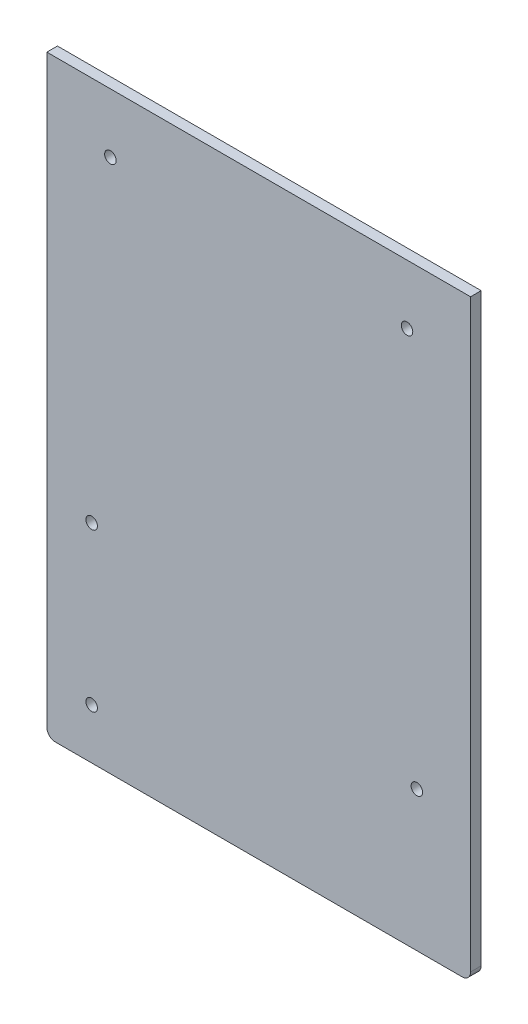
SolidWorks part; units mm, degrees
material "Acrylic (Medium-high impact)"
ref_plane "Front Plane" through (0, 0, 0) normal (0, 0, 1) x (1, 0, 0)
ref_plane "Top Plane" through (0, 0, 0) normal (0, 1, 0) x (1, 0, 0)
ref_plane "Right Plane" through (0, 0, 0) normal (1, 0, 0) x (0, 0, -1)
sketch "Sketch1" plane through (0, 0, 0) normal (0, 0, 1) x (1, 0, 0)
  line L1 (-134.9877, 109.7446) -> (-7.9877, 109.7446)
  line L2 (-134.9877, 109.7446) -> (-134.9877, -68.0554)
  line L3 (-134.9877, -68.0554) -> (-7.9877, -68.0554)
  line L4 (-7.9877, 109.7446) -> (-7.9877, -68.0554)
  dimension "D1" = 177.8
  dimension "D2" = 127
extrude "Boss-Extrude1" add sketch "Sketch1" along normal blind 3.175
sketch "Sketch8" plane through (0, 0, 3.175) normal (0, 0, 1) x (1, 0, 0)
  line L0 (-121.5503, -52.9588) -> (-121.5503, -5.7148) construction
  line L1 (-121.5503, -5.7148) -> (-24.0915, -26.1003) construction
  line L2 (-24.0915, -26.1003) -> (-121.5503, -52.9588) construction
  line L3 (-134.9877, 109.7446) -> (-134.9877, -68.0554) construction
  line L4 (-134.9877, -68.0554) -> (-7.9877, -68.0554) construction
  point P10 (-121.5503, -5.7148)
  point P11 (-121.5503, -52.9588)
  point P12 (-24.0915, -26.1003)
  dimension "D1" = 13.4374
  dimension "D2" = 97.4588
  dimension "D3" = 20.3855
  dimension "D4" = 15.0967
  dimension "D5" = 47.244
hole_wizard "#29 (0.136) Diameter Hole1" positions "Sketch9" profile "Sketch10" hole size "#29" standard "ANSI Inch" end condition through all
sketch "Sketch9" plane through (0, 0, 3.175) normal (0, 0, 1) x (1, 0, 0)
  line L0 (-115.9377, 91.9646) -> (-27.0377, 91.9646) construction
  line L2 (-71.4877, 91.9646) -> (-71.4877, 109.7446) construction
  line L3 (-7.9877, 109.7446) -> (-134.9877, 109.7446) construction
  point P69 (-27.0377, 91.9646)
  point P72 (-115.9377, 91.9646)
  dimension "D1" = 88.9
  dimension "D2" = 17.78
sketch "Sketch10" plane through (-27.0377, 91.9646, 3.175) normal (1, 0, 0) x (0, -1, 0)
  line L0 (0, 0) -> (0, 3.175)
  line L1 (0, 3.175) -> (1.7272, 3.175)
  line L2 (1.7272, 3.175) -> (1.7272, 0)
  line L5 (1.7272, 0) -> (0, 0)
  line L11 (0, -6.35) -> (0, 107.95) construction
  dimension "Thru Hole Dia." = 3.4544
  dimension "Thru Hole Depth" = 3.175
fillet "Fillet1" radius 2.54 2 edges at (-134.9877, -68.0554, 1.5875) (-7.9877, -68.0554, 1.5875)
hole_wizard "Tap Drill for #8-32 Tap1" positions "Sketch11" profile "Sketch12" hole size "#8-32" standard "ANSI Inch" end condition through all
sketch "Sketch11" plane through (0, 0, 3.175) normal (0, 0, 1) x (1, 0, 0)
  point P0 (-121.5503, -52.9588)
  point P3 (-121.5503, -5.7148)
  point P6 (-24.0915, -26.1003)
sketch "Sketch12" plane through (-121.5503, -52.9588, 3.175) normal (1, 0, 0) x (0, -1, 0)
  line L0 (0, 0) -> (0, 3.175)
  line L1 (0, 3.175) -> (1.7272, 3.175)
  line L2 (1.7272, 3.175) -> (1.7272, 0)
  line L5 (1.7272, 0) -> (0, 0)
  line L11 (0, -6.35) -> (0, 107.95) construction
  dimension "Thru Hole Dia." = 3.4544
  dimension "Thru Hole Depth" = 3.175
